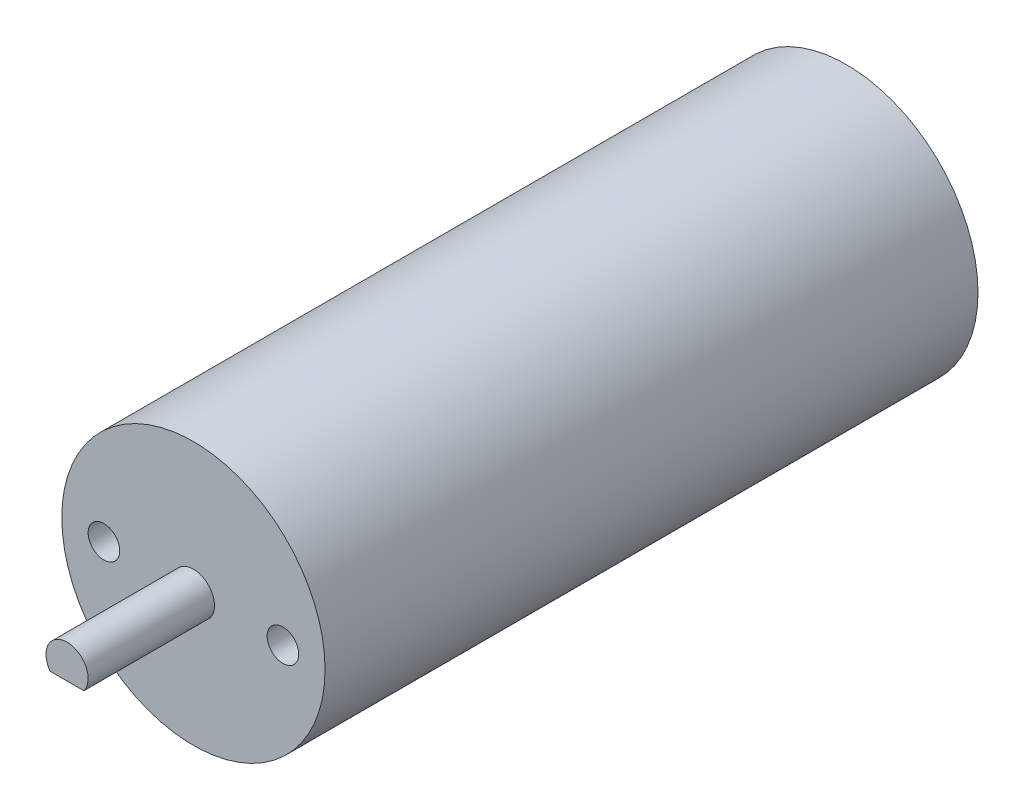
SolidWorks part; units mm, degrees
ref_plane "Přední rovina" through (0, 0, 0) normal (0, 0, 1) x (1, 0, 0)
ref_plane "Horní rovina" through (0, 0, 0) normal (0, 1, 0) x (1, 0, 0)
ref_plane "Pravá rovina" through (0, 0, 0) normal (1, 0, 0) x (0, 0, -1)
sketch "Skica1" plane through (0, 0, 0) normal (0, 0, 1) x (1, 0, 0)
  circle A0 centre (0, 0) radius 12.5
  dimension "D1" = 25
extrude "Přidat vysunutím1" add sketch "Skica1" along normal blind 62
sketch "Skica2" plane through (0, 0, 62) normal (0, 0, 1) x (1, 0, 0)
  line L0 (-1.6, -1.2) -> (1.6, -1.2)
  arc A0 (1.6, -1.2) -> (-1.6, -1.2) centre (0, 0) ccw
  dimension "D1" = 4
  dimension "D2" = 1.2
extrude "Přidat vysunutím2" add sketch "Skica2" along normal blind 12
sketch "Skica3" plane through (0, 0, 62) normal (0, 0, 1) x (1, 0, 0)
  line L0 (-12.5, 0) -> (12.5, 0) construction
  line L1 (0, 12.5) -> (0, -12.5) construction
  circle A0 centre (0, 0) radius 12.5 construction
  circle A1 centre (-8.5, 0) radius 1.5
  circle A2 centre (8.5, 0) radius 1.5
  dimension "D1" = 3
  dimension "D2" = 17
extrude "Odebrat vysunutím1" cut sketch "Skica3" against normal blind 4
